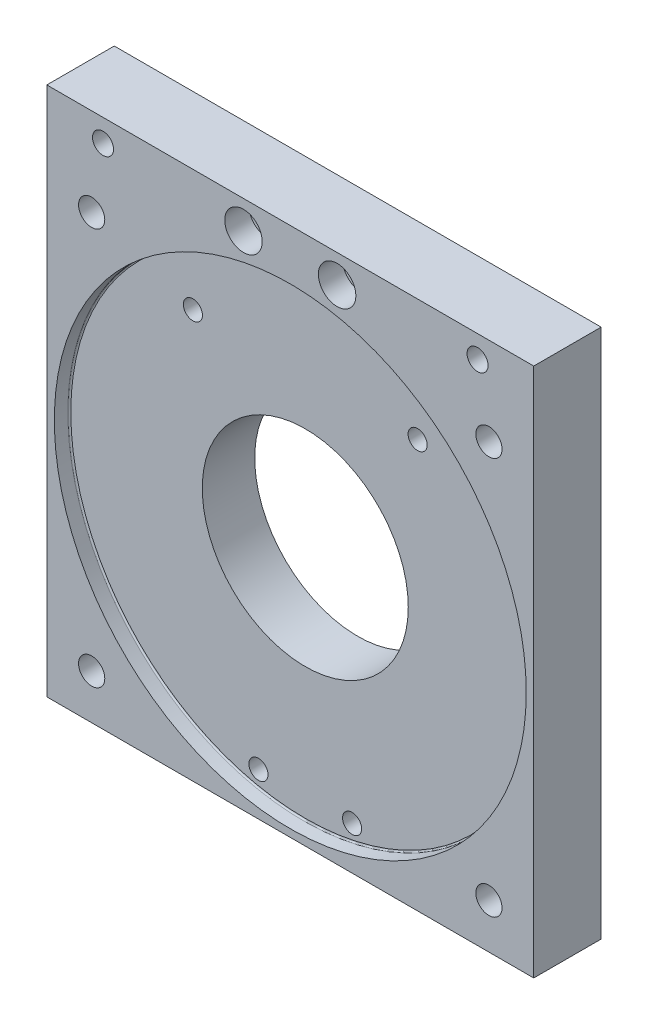
SolidWorks part; units mm, degrees
material "Low Carbon Steel"
ref_plane "Front Plane" through (0, 0, 0) normal (0, 0, 1) x (1, 0, 0)
ref_plane "Top Plane" through (0, 0, 0) normal (0, 1, 0) x (1, 0, 0)
ref_plane "Right Plane" through (0, 0, 0) normal (1, 0, 0) x (0, 0, -1)
sketch "Sketch1" plane through (0, 0, 0) normal (0, 0, 1) x (1, 0, 0)
  line L0 (-130, 130) -> (130, -130) construction
  line L1 (-130, 130) -> (130, 130) construction
  line L2 (-130, 130) -> (-130, -130)
  line L3 (-130, -130) -> (130, -130)
  line L4 (130, 130) -> (130, -130)
  line L5 (-130, 153) -> (130, 153)
  line L6 (130, 153) -> (130, 130)
  line L7 (-130, 153) -> (-130, 130)
  dimension "D1" = 260
  dimension "D2" = 260
  dimension "D3" = 46
extrude "Boss-Extrude1" add sketch "Sketch1" along normal blind 50.8
sketch "Sketch6" plane through (130, 0, 0) normal (1, 0, 0) x (0, 0, -1)
  line L0 (-50.8, -130) -> (0, -130) construction
  line L1 (0, 153) -> (-7.4, 153)
  line L2 (0, 153) -> (0, -130)
  line L3 (0, -130) -> (-7.4, -130)
  line L4 (-7.4, 153) -> (-7.4, -130)
  line L6 (-50.8, -130) -> (-43.4, -130)
  line L7 (-50.8, -130) -> (-50.8, 153)
  line L8 (-50.8, 153) -> (-43.4, 153)
  line L9 (-43.4, -130) -> (-43.4, 153)
  line L10 (-50.8, 153) -> (0, 153) construction
  line L13 (0, -130) -> (0, 153) construction
  dimension "D1" = 36
extrude "Cut-Extrude3" cut sketch "Sketch6" against normal through all
sketch "Sketch2" plane through (0, 0, 43.4) normal (0, 0, 1) x (1, 0, 0)
  circle A0 centre (0, 0) radius 126
  dimension "D1" = 252
extrude "Cut-Extrude1" cut sketch "Sketch2" against normal blind 8
hole_wizard "M16 Tapped Hole1" positions "Sketch4" profile "Sketch3" tap size "M16" standard "Peddi DIN" end condition through all
sketch "Sketch4" plane through (116.1053, 120.4836, 43.4) normal (0, 0, 1) x (1, 0, 0)
  line L0 (-10.0393, -14.4175) -> (-222.1713, -14.4175) construction
  line L2 (-222.1713, -226.5496) -> (-10.0393, -226.5496) construction
  line L3 (-10.0393, -226.5496) -> (-10.0393, -14.4175) construction
  circle A0 centre (-116.1053, -120.4836) radius 150 construction
  point P0 (-222.1713, -14.4175)
  point P2 (-10.0393, -14.4175)
  point P4 (-10.0393, -226.5496)
  point P6 (-222.1713, -226.5496)
  dimension "D1" = 300
cosmetic thread "Hole Thread5" parameters "D2"=16
cosmetic thread "Hole Thread6" parameters "D2"=16
cosmetic thread "Hole Thread7" parameters "D2"=16
cosmetic thread "Hole Thread8" parameters "D2"=16
sketch "Sketch3" plane through (-106.066, 106.066, 43.4) normal (1, 0, 0) x (0, -1, 0)
  line L0 (0, 0) -> (0, 36)
  line L1 (0, 36) -> (7, 36)
  line L2 (7, 36) -> (7, 0)
  line L5 (7, 0) -> (0, 0)
  line L11 (0, -6.35) -> (0, 107.95) construction
  dimension "Thru Tap Drill Dia." = 14
  dimension "Thru Tap Drill Depth" = 36
sketch "Sketch5" plane through (0, 0, 35.4) normal (0, 0, 1) x (1, 0, 0)
  circle A0 centre (0, 0) radius 55
  dimension "D1" = 110
extrude "Cut-Extrude2" cut sketch "Sketch5" against normal through all
fillet "Fillet1" radius 0.7937 1 edges at (126, 0, 35.4)
hole_wizard "CBORE for M12 Hex Socket Head Cap Screw1" positions "Sketch9" profile "Sketch8" counterbore size "M12" standard "Peddi DIN" end condition through all
sketch "Sketch9" plane through (0, 0, 43.4) normal (0, 0, 1) x (1, 0, 0)
  line L0 (25, 138) -> (-25, 138) construction
  line L2 (0, 138) -> (0, 0) construction
  point P0 (-25, 138)
  point P2 (25, 138)
  dimension "D1" = 50
  dimension "D2" = 138
sketch "Sketch8" plane through (-25, 138, 43.4) normal (1, 0, 0) x (0, -1, 0)
  line L0 (0, 0) -> (0, 36)
  line L1 (0, 36) -> (6.75, 36)
  line L3 (6.75, 36) -> (6.75, 13)
  line L4 (6.75, 13) -> (10, 13)
  line L5 (10, 13) -> (10, 0)
  line L7 (10, 0) -> (0, 0)
  line L11 (0, -6.35) -> (0, 107.95) construction
  dimension "Thru Hole Dia." = 13.5
  dimension "Thru Hole Depth" = 36
  dimension "C'Bore Dia." = 20
  dimension "C'Bore Depth" = 13
hole_wizard "M12 Tapped Hole1" positions "Sketch11" profile "Sketch10" tap size "M12" standard "Peddi DIN" end condition through all
sketch "Sketch11" plane through (0, 0, 7.4) normal (0, 0, -1) x (-1, 0, 0)
  line L0 (-60, 80) -> (60, 80) construction
  line L6 (0, 0) -> (0, 80) construction
  line L9 (-25, -115) -> (25, -115) construction
  line L11 (0, -115) -> (0, 0) construction
  circle A0 centre (0, 0) radius 55 construction
  point P0 (-60, 80)
  point P2 (60, 80)
  point P4 (25, -115)
  point P6 (-25, -115)
  dimension "D1" = 80
  dimension "D2" = 120
  dimension "D3" = 50
  dimension "D4" = 195
cosmetic thread "Hole Thread9" parameters "D2"=12
cosmetic thread "Hole Thread10" parameters "D2"=12
cosmetic thread "Hole Thread11" parameters "D2"=12
cosmetic thread "Hole Thread12" parameters "D2"=12
sketch "Sketch10" plane through (60, 80, 7.4) normal (1, 0, 0) x (0, 1, 0)
  line L0 (0, 0) -> (0, 36)
  line L1 (0, 36) -> (5.1, 36)
  line L2 (5.1, 36) -> (5.1, 0)
  line L5 (5.1, 0) -> (0, 0)
  line L11 (0, -6.35) -> (0, 107.95) construction
  dimension "Thru Tap Drill Dia." = 10.2
  dimension "Thru Tap Drill Depth" = 36
hole_wizard "M6 Tapped Hole1" positions "Sketch12" profile "Sketch13" tap size "M6" standard "Peddi DIN"
sketch "Sketch12" plane through (0, 0, 7.4) normal (0, 0, -1) x (-1, 0, 0)
  line L0 (100, 141) -> (-100, 141) construction
  line L3 (0, 141) -> (0, 0) construction
  line L7 (130, 153) -> (-130, 153) construction
  point P0 (100, 141)
  point P2 (-100, 141)
  dimension "D1" = 200
  dimension "D2" = 12
sketch "Sketch13" plane through (-100, 141, 7.4) normal (1, 0, 0) x (0, 1, 0)
  line L0 (0, 0) -> (0, 29.4922)
  line L1 (0, 29.4922) -> (2.5, 27.99)
  line L2 (2.5, 27.99) -> (2.5, 0)
  line L5 (2.5, 0) -> (0, 0)
  line L10 (0, 29.4922) -> (-2.5, 27.99) construction
  line L11 (0, -6.35) -> (0, 107.95) construction
  dimension "Tap Drill Dia." = 5
  dimension "Tap Drill Depth" = 27.99
  dimension "Drill Angle" = 118
cosmetic thread "Hole Thread13" parameters "D1"=15.01, "D2"=6
cosmetic thread "Hole Thread14" parameters "D1"=15.01, "D2"=6
hole_wizard "Ø11.2 (11.2) Diameter Hole1" positions "Sketch14" profile "Sketch15" hole size "Ø11.2" standard "Peddi DIN"
sketch "Sketch14" plane through (0, 0, 43.4) normal (0, 0, 1) x (1, 0, 0)
  point P0 (100, 141)
  point P3 (-100, 141)
sketch "Sketch15" plane through (100, 141, 43.4) normal (1, 0, 0) x (0, -1, 0)
  line L0 (0, 0) -> (0, 23.3648)
  line L1 (0, 23.3648) -> (5.6, 20)
  line L2 (5.6, 20) -> (5.6, 0)
  line L5 (5.6, 0) -> (0, 0)
  line L10 (0, 23.3648) -> (-5.6, 20) construction
  line L11 (0, -6.35) -> (0, 107.95) construction
  dimension "Hole Dia." = 11.2
  dimension "Hole Depth" = 20
  dimension "Drill Angle" = 118
other "Freeze***"
